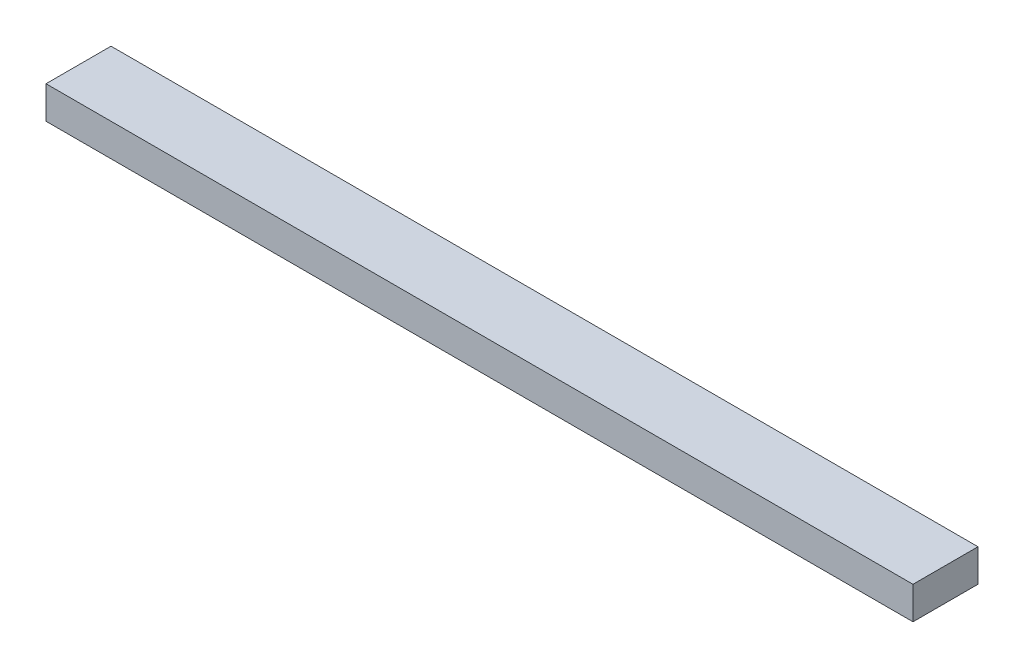
SolidWorks part; units mm, degrees
ref_plane "Front Plane" through (0, 0, 0) normal (0, 0, 1) x (1, 0, 0)
ref_plane "Top Plane" through (0, 0, 0) normal (0, 1, 0) x (1, 0, 0)
ref_plane "Right Plane" through (0, 0, 0) normal (1, 0, 0) x (0, 0, -1)
sketch "Sketch1" plane through (0, 0, 0) normal (0, 1, 0) x (1, 0, 0)
  line L1 (80, 6) -> (-80, 6)
  line L2 (80, 6) -> (80, -6)
  line L3 (80, -6) -> (-80, -6)
  line L4 (-80, 6) -> (-80, -6)
  line L5 (80, 6) -> (-80, -6) construction
  line L6 (80, -6) -> (-80, 6) construction
  point P0 (0, 0)
  dimension "D1" = 160
  dimension "D2" = 12
extrude "Boss-Extrude1" add sketch "Sketch1" along normal blind 6
